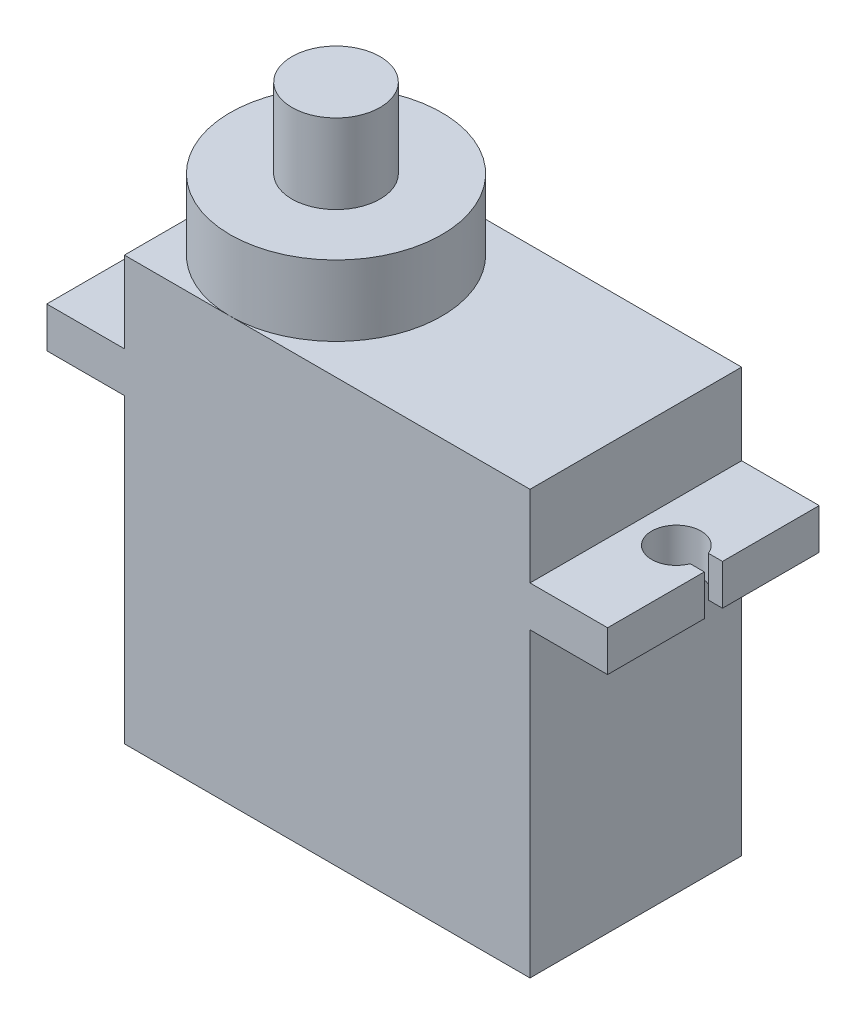
SolidWorks part; units mm, degrees
ref_plane "Alzado" through (0, 0, 0) normal (0, 0, 1) x (1, 0, 0)
ref_plane "Planta" through (0, 0, 0) normal (0, 1, 0) x (1, 0, 0)
ref_plane "Vista lateral" through (0, 0, 0) normal (1, 0, 0) x (0, 0, -1)
sketch "Croquis1" plane through (0, 0, 0) normal (0, 1, 0) x (1, 0, 0)
  line L1 (11.5, -6) -> (-11.5, -6)
  line L2 (11.5, -6) -> (11.5, 6)
  line L3 (11.5, 6) -> (-11.5, 6)
  line L4 (-11.5, -6) -> (-11.5, 6)
  line L5 (11.5, -6) -> (-11.5, 6) construction
  line L6 (11.5, 6) -> (-11.5, -6) construction
  point P0 (0, 0)
  dimension "D1" = 23
  dimension "D2" = 12
extrude "Saliente-Extruir1" add sketch "Croquis1" along normal blind 24
sketch "Croquis2" plane through (-11.5, 0, 0) normal (-1, 0, 0) x (0, 0, 1)
  line L0 (-6, 0) -> (-6, 17.1) construction
  line L1 (-6, 24) -> (-6, 0) construction
  line L2 (6, 24) -> (6, 0) construction
  line L3 (-6, 17.1) -> (6, 17.1)
  line L4 (-6, 17.1) -> (-6, 19.4)
  line L5 (-6, 19.4) -> (6, 19.4)
  line L6 (6, 17.1) -> (6, 19.4)
  dimension "D1" = 17.1
  dimension "D2" = 2.3
extrude "Saliente-Extruir2" add sketch "Croquis2" along normal blind 4.4
sketch "Croquis3" plane through (0, 19.4, 0) normal (0, 1, 0) x (1, 0, 0)
  line L0 (-11.5, 0) -> (-13.8, 0) construction
  line L2 (-11.5, 6) -> (-11.5, -6) construction
  line L3 (-15.9, -6) -> (-15.9, 6) construction
  line L4 (-15.1016, -0.5157) -> (-15.9, -0.5157)
  line L6 (-15.1016, 0.5157) -> (-15.9, 0.5157)
  line L7 (-15.9, -0.5157) -> (-15.9, 0.5157)
  arc A0 (-15.1016, -0.5157) -> (-15.1016, 0.5157) centre (-13.8, 0) ccw
  point P7 (-15.2, 0)
  dimension "D2" = 2.8
  dimension "D1" = 2.3
extrude "Cortar-Extruir1" cut sketch "Croquis3" against normal up to next
mirror "Simetría1" about plane through (0, 0, 0) normal (1, 0, 0) of "Cortar-Extruir1", "Saliente-Extruir2"
sketch "Croquis4" plane through (0, 24, 0) normal (0, 1, 0) x (1, 0, 0)
  line L0 (11.5, 6) -> (-11.5, 6) construction
  line L1 (-11.5, -6) -> (11.5, -6) construction
  line L2 (-11.5, 6) -> (-11.5, -6) construction
  circle A0 centre (-5.5, 0) radius 6
extrude "Saliente-Extruir4" add sketch "Croquis4" along normal blind 4
sketch "Croquis5" plane through (0, 28, 0) normal (0, 1, 0) x (1, 0, 0)
  circle A0 centre (-0.0495, -2.4165) radius 0.0378 construction
  circle A1 centre (-5.5, 0) radius 2.5
  dimension "D1" = 5
extrude "Saliente-Extruir5" add sketch "Croquis5" along normal blind 4.5
